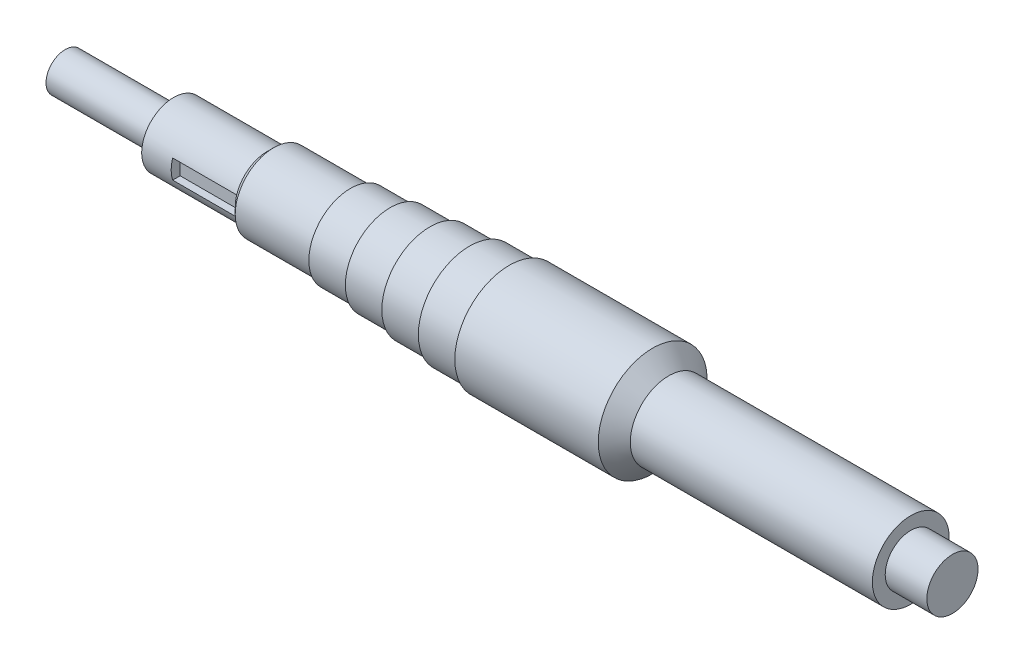
SolidWorks part; units mm, degrees
ref_plane "Front Plane" through (0, 0, 0) normal (0, 0, 1) x (1, 0, 0)
ref_plane "Top Plane" through (0, 0, 0) normal (0, 1, 0) x (1, 0, 0)
ref_plane "Right Plane" through (0, 0, 0) normal (1, 0, 0) x (0, 0, -1)
sketch "Sketch1" plane through (0, 0, 0) normal (0, 0, 1) x (1, 0, 0)
  line L0 (0, 0) -> (138.56, 0) construction
  line L4 (0, 0) -> (0, 3)
  line L5 (0, 3) -> (6.5, 3)
  line L11 (32.55, 6) -> (44.55, 6)
  line L12 (44.55, 6) -> (44.55, 6.5)
  line L13 (44.55, 6.5) -> (50.75, 6.5)
  line L17 (56.95, 7.5) -> (63.15, 7.5)
  line L18 (63.15, 7.5) -> (63.15, 8)
  line L31 (32.55, 6) -> (44.55, 6)
  line L36 (0, 0) -> (138.56, 0)
  line L38 (21.87, 5) -> (31.55, 5)
  line L40 (31.55, 5) -> (32.55, 6)
  line L41 (63.15, 8) -> (69.35, 8)
  line L42 (69.35, 8.5) -> (69.35, 8)
  line L43 (69.35, 8.5) -> (91.75, 8.5)
  line L44 (50.75, 6.5) -> (50.75, 7)
  line L45 (50.75, 7) -> (56.95, 7)
  line L46 (120.06, 6) -> (132.06, 6)
  line L47 (56.95, 7) -> (56.95, 7.5)
  line L48 (91.75, 8.5) -> (94.25, 6)
  line L49 (94.25, 6) -> (120.06, 6)
  line L50 (132.06, 6) -> (132.06, 4)
  line L51 (132.06, 4) -> (138.56, 4)
  line L52 (138.56, 4) -> (138.56, 0)
  line L54 (6.5, 3) -> (16.94, 3)
  line L55 (16.94, 3) -> (16.94, 5)
  line L56 (16.94, 5) -> (21.87, 5)
  point P3 (38.7596, 6)
  point P23 (44.436, 6)
  dimension "D13" = 3
  dimension "D12" = 6.5
  dimension "D5" = 9.68
  dimension "D6" = 5
  dimension "D7" = 6
  dimension "D8" = 45
  dimension "D9" = 12
  dimension "D10" = 6.2
  dimension "D3" = 6.2
  dimension "D4" = 6.2
  dimension "D15" = 22.4
  dimension "D18" = 8.5
  dimension "D11" = 25.81
  dimension "D19" = 6
  dimension "D20" = 45
  dimension "D21" = 6.2
  dimension "D16" = 12
  dimension "D17" = 4
  dimension "D22" = 6.5
  dimension "D14" = 10.44
  dimension "D23" = 4.93
revolve "Revolve1" add sketch "Sketch1" angle 360 about L0
sketch3d "3DSketch1" plane through (0, 0, 0) normal (0, 0, 1) x (1, 0, 0)
sketch "Sketch2" plane through (0, 0, 3) normal (0, 0, 1) x (1, 0, 0)
  line L0 (31.55, 5) -> (31.55, -5) construction
  line L1 (21.55, 1.5) -> (31.55, 1.5)
  line L2 (21.55, 1.5) -> (21.55, -1.5)
  line L3 (21.55, -1.5) -> (31.55, -1.5)
  line L4 (31.55, 1.5) -> (31.55, -1.5)
  line L5 (31.55, 5) -> (16.94, 5) construction
  point P4 (0, 0)
  dimension "D1" = 10
  dimension "D2" = 3
  dimension "D3" = 3.5
extrude "Cut-Extrude1" cut sketch "Sketch2" against normal blind 1.4 from offset 2
equation "\"Lab_Seal_Height\"= 0.089mm"
equation "\"Lab_Seal_Width\"= 12.7mm"
equation "\"LOx_Nut_Rad\"= 3mm"
equation "\"LOx_Nut_Len\" = 6.5mm"
equation "\"LOx_Taper_Len\" = 15.24mm"
equation "\"D13@Sketch1\"=\"LOx_Nut_Rad\""
equation "\"D12@Sketch1\"=\"LOx_Nut_Len\""
equation "\"LOx_Section_2\"= 9.68"
equation "\"LOx_End_Taper_Ang\"= 45deg"
equation "\"LOx_End_Rad\"= 5mm"
equation "\"D6@Sketch1\"=\"LOx_End_Rad\""
equation "\"D5@Sketch1\"=\"LOx_Section_2\""
equation "\"LOx_Bearing_Rad\"= 6mm"
equation "\"LOx_Bearing_Section_Width\" = 12mm"
equation "\"Lab_Seal_Len\"= 6.2mm"
equation "\"Lab_Seal_Stepup\"= .5"
equation "\"D7@Sketch1\"=\"LOx_Bearing_Rad\""
equation "\"D8@Sketch1\"=\"LOx_End_Taper_Ang\""
equation "\"D9@Sketch1\"=\"LOx_Bearing_Section_Width\""
equation "\"D10@Sketch1\"=\"Lab_Seal_Len\""
equation "\"D3@Sketch1\"=\"Lab_Seal_Len\""
equation "\"D4@Sketch1\"=\"Lab_Seal_Len\""
equation "\"Center_Section_Len\"= 22.4mm"
equation "\"Center_Section_Rad\"= 8.5mm"
equation "\"D15@Sketch1\"=\"Center_Section_Len\""
equation "\"D18@Sketch1\"=\"Center_Section_Rad\""
equation "\"Kero_Len\"= 25.81"
equation "\"Kero_Rad\" = 6mm"
equation "\"D11@Sketch1\"=\"Kero_Len\""
equation "\"D19@Sketch1\"=\"Kero_Rad\""
equation "\"D20@Sketch1\"=\"LOx_End_Taper_Ang\""
equation "\"D21@Sketch1\"=\"Lab_Seal_Len\""
equation "\"Shaft_Sleeve_Nut_Size\" = 4mm"
equation "\"Shaft_Sleeve_Nut_Width\" = 6.5mm"
equation "\"Distance to connection\"= 12mm"
equation "\"D16@Sketch1\"=\"Distance to connection\""
equation "\"D17@Sketch1\"=\"Shaft_Sleeve_Nut_Size\""
equation "\"D22@Sketch1\"=\"Shaft_Sleeve_Nut_Width\""
equation "\"LOx_Small_Section_Len\"= 10.44mm"
equation "\"D14@Sketch1\"=\"LOx_Small_Section_Len\""
equation "\"LOx_Keyway_Overhand\" = 4.93mm"
equation "\"D23@Sketch1\"=\"LOx_Keyway_Overhand\""
